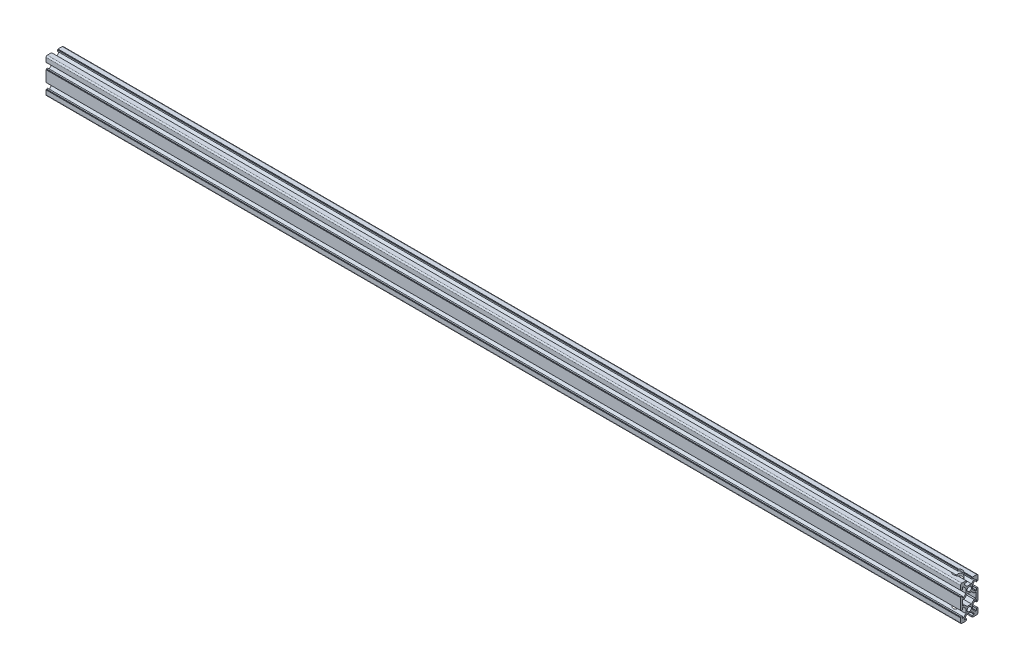
SolidWorks part; units mm, degrees
ref_plane "前视基准面" through (0, 0, 0) normal (0, 0, 1) x (1, 0, 0)
ref_plane "上视基准面" through (0, 0, 0) normal (0, 1, 0) x (1, 0, 0)
ref_plane "右视基准面" through (0, 0, 0) normal (1, 0, 0) x (0, 0, -1)
other "Configuration Table"
ref_plane "基准面1" through (0, 0, 9.923) normal (0, 0, 1) x (1, 0, 0)
sketch "草图1" plane through (0, 0, 9.923) normal (0, 0, 1) x (1, 0, 0)
  line L0 (-1048, 19.9963) -> (-1048, -20.0037)
  line L1 (-1048, -20.0037) -> (0, -20.0037)
  line L2 (0, -20.0037) -> (0, 19.9963)
  line L3 (0, 19.9963) -> (-1048, 19.9963)
extrude "凸台-拉伸1" add sketch "草图1" against normal blind 20
sketch "草图2" plane through (0, 0, 0) normal (1, 0, 0) x (0, 0, -1)
  line L0 (-3.023, 19.9963) -> (-3.023, 17.9963)
  line L1 (-3.023, 17.9963) -> (-5.423, 17.9963)
  line L2 (-5.423, 17.9963) -> (-5.423, 16.9105)
  line L3 (-5.423, 16.9105) -> (-2.4088, 13.8963)
  line L4 (-2.4088, 13.8963) -> (2.5628, 13.8963)
  line L5 (2.5628, 13.8963) -> (5.577, 16.9105)
  line L6 (5.577, 16.9105) -> (5.577, 17.9963)
  line L7 (5.577, 17.9963) -> (3.177, 17.9963)
  line L8 (3.177, 17.9963) -> (3.177, 19.9963)
  line L9 (3.177, 19.9963) -> (-3.023, 19.9963)
extrude "切除-拉伸1" cut sketch "草图2" against normal through all
sketch "草图3" plane through (0, 19.9963, 0) normal (0, 1, 0) x (-1, 0, 0)
  line L0 (9.0173, 3.023) -> (16.9827, 3.023)
  arc A0 (16.9827, 3.023) -> (9.0173, 3.023) centre (13, 0) ccw
extrude "切除-拉伸2" cut sketch "草图3" against normal up to next
sketch "草图4" plane through (-1048, 0, 0) normal (-1, 0, 0) x (0, 0, 1)
  line L0 (3.023, 19.4963) -> (3.628, 19.4963)
  line L1 (3.628, 19.4963) -> (3.628, 19.9963)
  line L2 (3.628, 19.9963) -> (3.023, 19.9963)
  line L3 (3.023, 19.9963) -> (3.023, 19.4963)
extrude "切除-拉伸3" cut sketch "草图4" against normal up to next
sketch "草图5" plane through (0, 0, 0) normal (1, 0, 0) x (0, 0, -1)
  line L0 (-3.023, -20.0037) -> (3.177, -20.0037)
  line L1 (3.177, -20.0037) -> (3.177, -18.0037)
  line L2 (3.177, -18.0037) -> (5.577, -18.0037)
  line L3 (5.577, -18.0037) -> (5.577, -16.9179)
  line L4 (5.577, -16.9179) -> (2.5628, -13.9037)
  line L5 (2.5628, -13.9037) -> (-2.4088, -13.9037)
  line L6 (-2.4088, -13.9037) -> (-5.423, -16.9179)
  line L7 (-5.423, -16.9179) -> (-5.423, -18.0037)
  line L8 (-5.423, -18.0037) -> (-3.023, -18.0037)
  line L9 (-3.023, -18.0037) -> (-3.023, -20.0037)
extrude "切除-拉伸4" cut sketch "草图5" against normal through all
sketch "草图6" plane through (0, -18.0037, 0) normal (0, 1, 0) x (-1, 0, 0)
  line L0 (9.0173, 3.023) -> (16.9827, 3.023)
  arc A0 (16.9827, 3.023) -> (9.0173, 3.023) centre (13, 0) ccw
extrude "切除-拉伸5" cut sketch "草图6" against normal through all
sketch "草图7" plane through (-1048, 0, 0) normal (-1, 0, 0) x (0, 0, 1)
  line L0 (3.023, -20.0037) -> (3.628, -20.0037)
  line L1 (3.628, -20.0037) -> (3.628, -19.5037)
  line L2 (3.628, -19.5037) -> (3.023, -19.5037)
  line L3 (3.023, -19.5037) -> (3.023, -20.0037)
extrude "切除-拉伸6" cut sketch "草图7" against normal up to next
sketch "草图8" plane through (0, -20.0037, 0) normal (0, -1, 0) x (1, 0, 0)
  line L0 (-9.1391, -3.177) -> (-16.8609, -3.177)
  arc A0 (-16.8609, -3.177) -> (-9.1391, -3.177) centre (-13, 0) ccw
extrude "切除-拉伸7" cut sketch "草图8" against normal up to next
sketch "草图9" plane through (-1048, 0, 0) normal (-1, 0, 0) x (0, 0, 1)
  line L0 (-3.177, -20.0037) -> (-3.177, -19.5037)
  line L1 (-3.177, -19.5037) -> (-3.782, -19.5037)
  line L2 (-3.782, -19.5037) -> (-3.782, -20.0037)
  line L3 (-3.782, -20.0037) -> (-3.177, -20.0037)
extrude "切除-拉伸8" cut sketch "草图9" against normal up to next
sketch "草图10" plane through (0, 0, 0) normal (1, 0, 0) x (0, 0, -1)
  line L0 (-3.628, 19.9963) -> (-3.628, 19.4963)
  line L1 (-3.628, 19.4963) -> (-3.023, 19.4963)
  line L2 (-3.023, 19.4963) -> (-3.023, 19.9963)
  line L3 (-3.023, 19.9963) -> (-3.628, 19.9963)
extrude "切除-拉伸9" cut sketch "草图10" against normal up to next
sketch "草图11" plane through (0, 17.9963, 0) normal (0, -1, 0) x (1, 0, 0)
  line L0 (-9.1391, -3.177) -> (-16.8609, -3.177)
  arc A0 (-16.8609, -3.177) -> (-9.1391, -3.177) centre (-13, 0) ccw
extrude "切除-拉伸10" cut sketch "草图11" against normal through all
sketch "草图12" plane through (0, 0, 0) normal (1, 0, 0) x (0, 0, -1)
  line L0 (3.177, 19.9963) -> (3.177, 19.4963)
  line L1 (3.177, 19.4963) -> (3.782, 19.4963)
  line L2 (3.782, 19.4963) -> (3.782, 19.9963)
  line L3 (3.782, 19.9963) -> (3.177, 19.9963)
extrude "切除-拉伸11" cut sketch "草图12" against normal up to next
sketch "草图13" plane through (0, 0, 0) normal (1, 0, 0) x (0, 0, -1)
  line L0 (10.077, 13.7013) -> (9.577, 13.7013)
  line L1 (9.577, 13.7013) -> (9.577, 13.0963)
  line L2 (9.577, 13.0963) -> (8.077, 13.0963)
  line L3 (8.077, 13.0963) -> (8.077, 15.4963)
  line L4 (8.077, 15.4963) -> (6.9912, 15.4963)
  line L5 (6.9912, 15.4963) -> (3.977, 12.4821)
  line L6 (3.977, 12.4821) -> (3.977, 7.5105)
  line L7 (3.977, 7.5105) -> (6.9912, 4.4963)
  line L8 (6.9912, 4.4963) -> (8.077, 4.4963)
  line L9 (8.077, 4.4963) -> (8.077, 6.8963)
  line L10 (8.077, 6.8963) -> (9.577, 6.8963)
  line L11 (9.577, 6.8963) -> (9.577, 6.2913)
  line L12 (9.577, 6.2913) -> (10.077, 6.2913)
  line L13 (10.077, 6.2913) -> (10.077, 13.7013)
extrude "切除-拉伸12" cut sketch "草图13" against normal through all
sketch "草图14" plane through (0, 0, 0) normal (1, 0, 0) x (0, 0, -1)
  line L0 (10.077, -6.2987) -> (9.577, -6.2987)
  line L1 (9.577, -6.2987) -> (9.577, -6.9037)
  line L2 (9.577, -6.9037) -> (8.077, -6.9037)
  line L3 (8.077, -6.9037) -> (8.077, -4.5037)
  line L4 (8.077, -4.5037) -> (6.9912, -4.5037)
  line L5 (6.9912, -4.5037) -> (3.977, -7.5179)
  line L6 (3.977, -7.5179) -> (3.977, -12.4895)
  line L7 (3.977, -12.4895) -> (6.9912, -15.5037)
  line L8 (6.9912, -15.5037) -> (8.077, -15.5037)
  line L9 (8.077, -15.5037) -> (8.077, -13.1037)
  line L10 (8.077, -13.1037) -> (9.577, -13.1037)
  line L11 (9.577, -13.1037) -> (9.577, -13.7087)
  line L12 (9.577, -13.7087) -> (10.077, -13.7087)
  line L13 (10.077, -13.7087) -> (10.077, -6.2987)
extrude "切除-拉伸13" cut sketch "草图14" against normal through all
sketch "草图15" plane through (0, 0, 0) normal (1, 0, 0) x (0, 0, -1)
  line L0 (3.782, -20.0037) -> (3.782, -19.5037)
  line L1 (3.782, -19.5037) -> (3.177, -19.5037)
  line L2 (3.177, -19.5037) -> (3.177, -20.0037)
  line L3 (3.177, -20.0037) -> (3.782, -20.0037)
extrude "切除-拉伸14" cut sketch "草图15" against normal up to next
sketch "草图16" plane through (0, 0, 0) normal (1, 0, 0) x (0, 0, -1)
  line L0 (-3.023, -20.0037) -> (-3.023, -19.5037)
  line L1 (-3.023, -19.5037) -> (-3.628, -19.5037)
  line L2 (-3.628, -19.5037) -> (-3.628, -20.0037)
  line L3 (-3.628, -20.0037) -> (-3.023, -20.0037)
extrude "切除-拉伸15" cut sketch "草图16" against normal up to next
sketch "草图17" plane through (0, 0, 0) normal (1, 0, 0) x (0, 0, -1)
  line L0 (-9.923, -13.7087) -> (-9.423, -13.7087)
  line L1 (-9.423, -13.7087) -> (-9.423, -13.1037)
  line L2 (-9.423, -13.1037) -> (-7.923, -13.1037)
  line L3 (-7.923, -13.1037) -> (-7.923, -15.5037)
  line L4 (-7.923, -15.5037) -> (-6.8372, -15.5037)
  line L5 (-6.8372, -15.5037) -> (-3.823, -12.4895)
  line L6 (-3.823, -12.4895) -> (-3.823, -7.5179)
  line L7 (-3.823, -7.5179) -> (-6.8372, -4.5037)
  line L8 (-6.8372, -4.5037) -> (-7.923, -4.5037)
  line L9 (-7.923, -4.5037) -> (-7.923, -6.9037)
  line L10 (-7.923, -6.9037) -> (-9.423, -6.9037)
  line L11 (-9.423, -6.9037) -> (-9.423, -6.2987)
  line L12 (-9.423, -6.2987) -> (-9.923, -6.2987)
  line L13 (-9.923, -6.2987) -> (-9.923, -13.7087)
extrude "切除-拉伸16" cut sketch "草图17" against normal through all
sketch "草图18" plane through (0, 0, 0) normal (1, 0, 0) x (0, 0, -1)
  line L0 (-9.923, 6.2913) -> (-9.423, 6.2913)
  line L1 (-9.423, 6.2913) -> (-9.423, 6.8963)
  line L2 (-9.423, 6.8963) -> (-7.923, 6.8963)
  line L3 (-7.923, 6.8963) -> (-7.923, 4.4963)
  line L4 (-7.923, 4.4963) -> (-6.8372, 4.4963)
  line L5 (-6.8372, 4.4963) -> (-3.823, 7.5105)
  line L6 (-3.823, 7.5105) -> (-3.823, 12.4821)
  line L7 (-3.823, 12.4821) -> (-6.8372, 15.4963)
  line L8 (-6.8372, 15.4963) -> (-7.923, 15.4963)
  line L9 (-7.923, 15.4963) -> (-7.923, 13.0963)
  line L10 (-7.923, 13.0963) -> (-9.423, 13.0963)
  line L11 (-9.423, 13.0963) -> (-9.423, 13.7013)
  line L12 (-9.423, 13.7013) -> (-9.923, 13.7013)
  line L13 (-9.923, 13.7013) -> (-9.923, 6.2913)
extrude "切除-拉伸17" cut sketch "草图18" against normal through all
sketch "草图19" plane through (-1048, 0, 0) normal (-1, 0, 0) x (0, 0, 1)
  line L0 (-3.782, 19.9963) -> (-3.782, 19.4963)
  line L1 (-3.782, 19.4963) -> (-3.177, 19.4963)
  line L2 (-3.177, 19.4963) -> (-3.177, 19.9963)
  line L3 (-3.177, 19.9963) -> (-3.782, 19.9963)
extrude "切除-拉伸18" cut sketch "草图19" against normal up to next
sketch "草图20" plane through (-1048, 0, 0) normal (-1, 0, 0) x (0, 0, 1)
  line L0 (2.4088, -3.0895) -> (7.423, -3.0895)
  line L1 (7.423, -3.0895) -> (7.423, 3.0821)
  line L2 (7.423, 3.0821) -> (2.4088, 3.0821)
  line L3 (2.4088, 3.0821) -> (2.4088, 6.0963)
  line L4 (2.4088, 6.0963) -> (-2.5628, 6.0963)
  line L5 (-2.5628, 6.0963) -> (-2.5628, 3.0821)
  line L6 (-2.5628, 3.0821) -> (-7.577, 3.0821)
  line L7 (-7.577, 3.0821) -> (-7.577, -3.0895)
  line L8 (-7.577, -3.0895) -> (-2.5628, -3.0895)
  line L9 (-2.5628, -3.0895) -> (-2.5628, -6.1037)
  line L10 (-2.5628, -6.1037) -> (2.4088, -6.1037)
  line L11 (2.4088, -6.1037) -> (2.4088, -3.0895)
extrude "切除-拉伸19" cut sketch "草图20" against normal through all
draft "拔模1" type of draft neutral plane draft angle 45 faces to draft 2 face at (-524, -4.5966, 2.4088) face at (-524, -4.5966, -2.5628) neutral plane through (0, -6.1037, -2.5628) neutral plane normal (0, 1, 0) parameters "D1"=45
draft "拔模2" type of draft neutral plane draft angle 45 faces to draft 2 face at (-524, 4.5892, -2.5628) face at (-524, 4.5892, 2.4088) neutral plane through (0, 6.0963, 2.4088) neutral plane normal (0, -1, 0) parameters "D1"=45
ref_plane "基准面2" through (0, 0, 0) normal (0, 0, -1) x (-1, 0, 0)
sketch "草图21" plane through (0, 0, 0) normal (0, 0, -1) x (-1, 0, 0)
  line L0 (8, 10.9963) -> (13, 10.9963)
  line L1 (13, 10.9963) -> (13, 16.4875)
  line L2 (13, 16.4875) -> (8, 16.4875)
  line L3 (8, 16.4875) -> (8, 10.9963)
  line L4 (13, 10.9963) -> (13, 16.4875) construction
revolve "切除-旋转1" cut sketch "草图21" angle 360 about L4
sketch "草图22" plane through (0, 0, 0) normal (0, 0, 1) x (1, 0, 0)
  line L0 (-8, -10.9963) -> (-13, -10.9963)
  line L1 (-13, -10.9963) -> (-13, -16.4949)
  line L2 (-13, -16.4949) -> (-8, -16.4949)
  line L3 (-8, -16.4949) -> (-8, -10.9963)
  line L4 (-13, -10.9963) -> (-13, -16.4949) construction
revolve "切除-旋转2" cut sketch "草图22" angle 360 about L4
hole_wizard "Ø5.0 (5) 直径孔1" positions "草图24" profile "草图23" hole size "Ø5.0" standard "ANSI Metric"
sketch "草图24" plane through (0, 0, 0) normal (1, 0, 0) x (0, 0, -1)
  point P0 (0.077, 9.9963)
sketch "草图23" plane through (0, 9.9963, -0.077) normal (0, 1, 0) x (0, 0, -1)
  line L0 (0, 0) -> (0, 1048)
  line L1 (0, 1048) -> (2.5, 1048)
  line L2 (2.5, 1048) -> (2.5, 0)
  line L5 (2.5, 0) -> (0, 0)
  line L11 (0, -6.35) -> (0, 107.95) construction
  dimension "通孔孔直径" = 5
  dimension "通孔孔深度" = 1048
hole_wizard "Ø5.0 (5) 直径孔2" positions "草图26" profile "草图25" hole size "Ø5.0" standard "ANSI Metric"
sketch "草图26" plane through (-1048, 0, 0) normal (-1, 0, 0) x (0, 0, 1)
  point P0 (-0.077, -10.0037)
sketch "草图25" plane through (-1048, -10.0037, -0.077) normal (0, 1, 0) x (0, 0, 1)
  line L0 (0, 0) -> (0, 1048)
  line L1 (0, 1048) -> (2.5, 1048)
  line L2 (2.5, 1048) -> (2.5, 0)
  line L5 (2.5, 0) -> (0, 0)
  line L11 (0, -6.35) -> (0, 107.95) construction
  dimension "通孔孔直径" = 5
  dimension "通孔孔深度" = 1048
fillet "圆角1" radius 1.5 4 edges at (-524, 19.9963, -10.077) (-524, -20.0037, -10.077) (-524, 19.9963, 9.923) (-524, -20.0037, 9.923)
